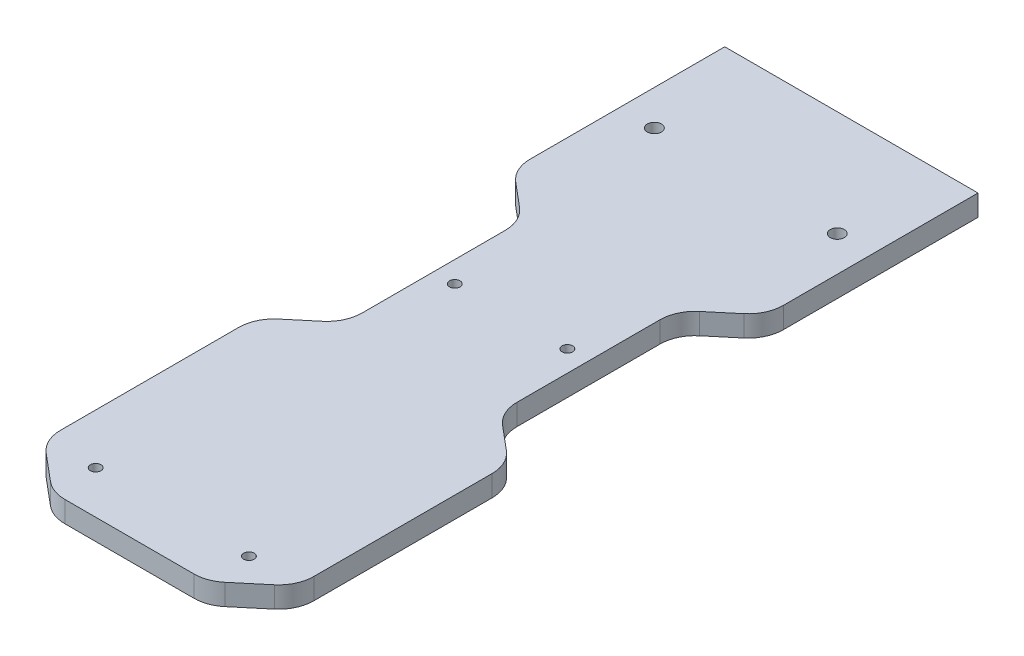
SolidWorks part; units mm, degrees
ref_plane "Front Plane" through (0, 0, 0) normal (0, 0, 1) x (1, 0, 0)
ref_plane "Top Plane" through (0, 0, 0) normal (0, 1, 0) x (1, 0, 0)
ref_plane "Right Plane" through (0, 0, 0) normal (1, 0, 0) x (0, 0, -1)
sketch "Sketch1" plane through (0, 0, 0) normal (0, 1, 0) x (1, 0, 0)
  line L0 (21.2131, -102.2276) -> (35.2131, -90.4802)
  line L1 (35.2131, -90.4802) -> (35.2131, -30.4802)
  line L2 (35.2131, -30.4802) -> (21.2131, -18.7328)
  line L3 (21.2131, -18.7328) -> (21.2131, 31.2672)
  line L4 (21.2131, 31.2672) -> (35.2131, 43.0146)
  line L5 (35.2131, 43.0146) -> (35.2131, 103.0146)
  line L6 (35.2131, 103.0146) -> (-36.7869, 103.0146)
  line L7 (-36.7869, 103.0146) -> (-36.7869, 43.0146)
  line L8 (-36.7869, 43.0146) -> (-22.7869, 31.2672)
  line L9 (-22.7869, 31.2672) -> (-22.7869, -18.7328)
  line L10 (-22.7869, -18.7328) -> (-36.7869, -30.4802)
  line L11 (-36.7869, -30.4802) -> (-36.7869, -90.4802)
  line L12 (-36.7869, -90.4802) -> (-22.7869, -102.2276)
  line L13 (-22.7869, -102.2276) -> (21.2131, -102.2276)
extrude "Boss-Extrude1" add sketch "Sketch1" along normal blind 6
fillet "Fillet1" radius 10 8 edges at (35.2131, 3, 30.4802) (21.2131, 3, 18.7328) (-22.7869, 3, 18.7328) (-36.7869, 3, 30.4802) (35.2131, 3, 90.4802) (21.2131, 3, 102.2276) (-22.7869, 3, 102.2276) (-36.7869, 3, 90.4802)
sketch "Sketch2" plane through (0, 0, 0) normal (0, -1, 0) x (1, 0, 0)
  line L1 (-36.7869, 60.4802) -> (21.737, 60.4802) construction
  line L2 (-36.7869, 35.1433) -> (-36.7869, 85.8172) construction
  circle A0 centre (-0.7869, 60.4802) radius 2.5
  dimension "D2" = 5
  dimension "D1" = 36
extrude "Cut-Extrude1" cut sketch "Sketch2" against normal blind 6
sketch "Sketch4" plane through (0, 0, 0) normal (0, -1, 0) x (1, 0, 0)
  line L0 (35.2131, -43.0146) -> (35.2131, -103.0146) construction
  line L1 (-36.7869, -103.0146) -> (35.2131, -103.0146)
  line L2 (-36.7869, -103.0146) -> (-36.7869, -99.0146)
  line L3 (-36.7869, -99.0146) -> (35.2131, -99.0146)
  line L4 (35.2131, -103.0146) -> (35.2131, -99.0146)
  dimension "D1" = 4
sketch "Sketch5" plane through (0, 0, 0) normal (0, -1, 0) x (1, 0, 0)
  circle A0 centre (-0.7869, 60.4802) radius 5.9976
extrude "Boss-Extrude2" add sketch "Sketch5" against normal blind 6
fillet "Fillet2" radius 10 4 edges at (35.2131, 3, -43.0146) (-36.7869, 3, -43.0146) (21.2131, 3, -31.2672) (-22.7869, 3, -31.2672)
sketch "Sketch6" plane through (0, 6, 0) normal (0, 1, 0) x (1, 0, 0)
  line L0 (21.2131, -14.0698) -> (21.2131, 26.6041) construction
  line L1 (-22.7869, 26.6041) -> (-22.7869, -14.0698) construction
  circle A0 centre (15.2131, 6.2672) radius 1.5
  circle A1 centre (-16.7869, 6.2672) radius 1.5
  dimension "D1" = 6
  dimension "D2" = 3
  dimension "D3" = 6
extrude "Cut-Extrude2" cut sketch "Sketch6" against normal blind 10
sketch "Sketch7" plane through (0, 6, 0) normal (0, 1, 0) x (1, 0, 0)
  circle A0 centre (20.9936, -90.0433) radius 1.5
  circle A1 centre (-22.5674, -90.0433) radius 1.5
extrude "Cut-Extrude3" cut sketch "Sketch7" against normal blind 10
sketch "Sketch8" plane through (0, 0, 0) normal (0, -1, 0) x (-1, 0, 0)
  line L0 (36.7869, 103.0146) -> (36.7869, 47.6776) construction
  line L1 (-35.2131, 103.0146) -> (36.7869, 103.0146) construction
  line L2 (-35.2131, 47.6776) -> (-35.2131, 103.0146) construction
  circle A0 centre (26.7869, 73.0146) radius 2
  circle A1 centre (-25.2131, 73.0146) radius 2
  dimension "D1" = 10
  dimension "D2" = 4
  dimension "D3" = 30
  dimension "D4" = 10
  dimension "D5" = 30
  dimension "D6" = 4
extrude "Cut-Extrude4" cut sketch "Sketch8" against normal blind 10
